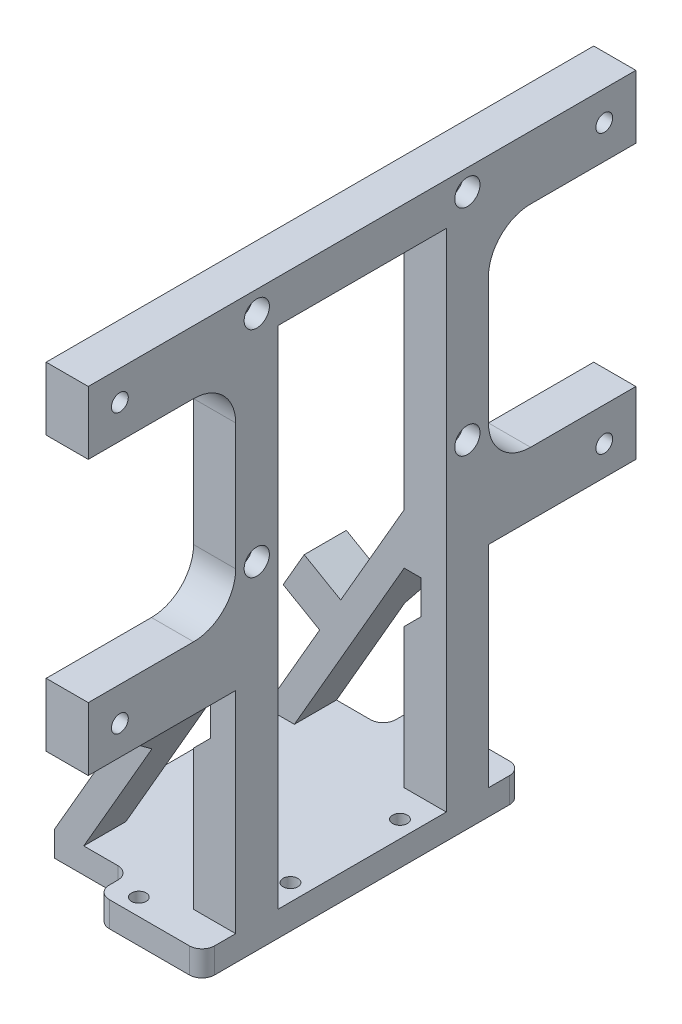
SolidWorks part; units mm, degrees
material "黄铜"
ref_plane "前视基准面" through (0, 0, 0) normal (0, 0, 1) x (1, 0, 0)
ref_plane "上视基准面" through (0, 0, 0) normal (0, 1, 0) x (1, 0, 0)
ref_plane "右视基准面" through (0, 0, 0) normal (1, 0, 0) x (0, 0, -1)
sketch "草图1" plane through (0, 0, 0) normal (0, 1, 0) x (1, 0, 0)
  line L1 (0, 0) -> (35, 0)
  line L2 (0, 0) -> (0, 60)
  line L3 (0, 60) -> (35, 60)
  line L4 (35, 0) -> (35, 60)
  line L5 (35, 60) -> (43, 60)
  line L6 (35, 60) -> (35, 0)
  line L7 (35, 0) -> (43, 0)
  line L8 (43, 60) -> (43, 0)
  line L9 (43, 60) -> (18, 60)
  line L10 (43, 60) -> (43, 68)
  line L11 (43, 68) -> (18, 68)
  line L12 (18, 60) -> (18, 68)
  line L13 (43, 0) -> (18, 0)
  line L14 (43, 0) -> (43, -8)
  line L15 (43, -8) -> (18, -8)
  line L16 (18, 0) -> (18, -8)
  dimension "D1" = 60
  dimension "D2" = 35
  dimension "D3" = 8
  dimension "D4" = 25
  dimension "D5" = 25
  dimension "D6" = 8
  dimension "D7" = 8
extrude "凸台-拉伸1" add sketch "草图1" along normal blind 6 contours L12 L3 L5 L10 L11 | L1 L4 L3 L2 | L8 L5 L4 L7 | L1 L16 L15 L14 L7
sketch "草图2" plane through (0, 6, 0) normal (0, 1, 0) x (1, 0, 0)
  line L0 (18, 64) -> (43, 64)
  line L1 (18, 60) -> (18, 68) construction
  line L2 (43, -8) -> (43, 68) construction
  line L3 (18, -4) -> (43, -4)
  line L4 (18, 0) -> (18, -8) construction
  line L5 (39, 68) -> (39, -8)
  line L6 (43, 68) -> (18, 68) construction
  line L7 (43, -8) -> (18, -8) construction
  point P6 (24, 64)
  point P11 (24, -4)
  point P18 (39, 43)
  point P19 (39, 17)
  dimension "D1" = 6
  dimension "D2" = 6
  dimension "D3" = 4
  dimension "D4" = 25
  dimension "D5" = 25
sketch "草图3" plane through (0, 6, 0) normal (0, 1, 0) x (1, 0, 0)
  point P0 (24, 64)
  point P3 (39, 43)
  point P6 (39, 17)
  point P9 (24, -4)
hole_wizard "孔1" positions "草图3" profile "草图4" legacy end condition through all
sketch "草图4" plane through (24, 6, -64) normal (1, 0, 0) x (0, 0, 1)
  line L0 (0, 0) -> (0, 6)
  line L1 (0, 6) -> (1.75, 6)
  line L2 (1.75, 6) -> (1.75, 0)
  line L3 (1.75, 0) -> (0, 0)
  line L4 (0, 110) -> (0, -10) construction
  dimension "直径" = 3.5
  dimension "深度" = 6
fillet "圆角1" radius 3 5 edges at (18, 3, -68) (43, 3, -68) (43, 3, 8) (18, 3, 8) (18, 3, 0)
sketch "草图5" plane through (0, 6, 0) normal (0, 1, 0) x (1, 0, 0)
  line L0 (43, -5) -> (43, 65) construction
  line L1 (43, 60) -> (33, 60)
  line L2 (43, 60) -> (43, 50)
  line L3 (43, 50) -> (33, 50)
  line L4 (33, 60) -> (33, 50)
  line L5 (0, 60) -> (18, 60) construction
  line L7 (43, 0) -> (33, 0)
  line L8 (43, 0) -> (43, 10)
  line L9 (43, 10) -> (33, 10)
  line L10 (33, 0) -> (33, 10)
  line L11 (0, 0) -> (15, 0) construction
  dimension "D1" = 10
  dimension "D2" = 10
  dimension "D3" = 10
  dimension "D4" = 10
extrude "凸台-拉伸2" add sketch "草图5" along normal blind 120
sketch "草图10" plane through (0, 126, 0) normal (0, 1, 0) x (1, 0, 0)
  line L1 (33, 60) -> (43, 60)
  line L2 (33, 60) -> (33, 0)
  line L3 (33, 0) -> (43, 0)
  line L4 (43, 60) -> (43, 0)
extrude "凸台-拉伸5" add sketch "草图10" along normal blind 10
sketch "草图11" plane through (43, 0, 0) normal (1, 0, 0) x (0, 0, -1)
  line L0 (0, 136) -> (0, 6) construction
  line L1 (0, 136) -> (10, 136)
  line L2 (0, 136) -> (0, 126)
  line L3 (0, 126) -> (10, 126)
  line L4 (10, 136) -> (10, 126)
  line L5 (50, 126) -> (60, 126)
  line L6 (50, 126) -> (50, 136)
  line L7 (50, 136) -> (60, 136)
  line L8 (60, 126) -> (60, 136)
  line L9 (0, 85) -> (10, 85)
  line L10 (0, 85) -> (0, 75)
  line L11 (0, 75) -> (10, 75)
  line L12 (10, 85) -> (10, 75)
  line L13 (10, 126) -> (10, 6) construction
  line L14 (50, 126) -> (50, 6) construction
  line L15 (50, 85) -> (60, 85)
  line L16 (50, 85) -> (50, 75)
  line L17 (50, 75) -> (60, 75)
  line L18 (60, 85) -> (60, 75)
  line L19 (60, 136) -> (60, 6) construction
  line L20 (0, 136) -> (10, 126)
  line L21 (60, 136) -> (50, 126)
  line L22 (0, 75) -> (10, 85)
  line L23 (60, 75) -> (50, 85)
  dimension "D1" = 61
  dimension "D2" = 10
  dimension "D3" = 61
  dimension "D4" = 10
sketch "草图12" plane through (43, 0, 0) normal (1, 0, 0) x (0, 0, -1)
  line L0 (0, 136) -> (10, 126) construction
  line L1 (60, 136) -> (50, 126) construction
  line L2 (60, 75) -> (50, 85) construction
  line L3 (0, 75) -> (10, 85) construction
  point P0 (5, 131)
  point P4 (55, 131)
  point P8 (55, 80)
  point P12 (5, 80)
hole_wizard "孔2" positions "草图12" profile "草图13" legacy end condition through all
sketch "草图13" plane through (43, 131, -5) normal (0, 1, 0) x (0, 0, -1)
  line L0 (0, 0) -> (0, 43)
  line L1 (0, 43) -> (1.75, 43)
  line L2 (1.75, 43) -> (1.75, 0)
  line L3 (1.75, 0) -> (0, 0)
  line L4 (0, 110) -> (0, -10) construction
  dimension "直径" = 3.5
  dimension "深度" = 43
sketch "草图14" plane through (43, 0, 0) normal (1, 0, 0) x (0, 0, -1)
  line L0 (0, 136) -> (10, 126) construction
  line L1 (0, 75) -> (10, 85) construction
  line L2 (60, 75) -> (50, 85) construction
  line L3 (60, 136) -> (50, 126) construction
  point P0 (5, 131)
  point P4 (5, 80)
  point P8 (55, 80)
  point P12 (55, 131)
hole_wizard "孔3" positions "草图14" profile "草图15" legacy
sketch "草图15" plane through (43, 131, -5) normal (0, 1, 0) x (0, 0, -1)
  line L0 (0, 0) -> (0, 4)
  line L1 (0, 4) -> (3, 4)
  line L2 (3, 4) -> (3, 0)
  line L3 (3, 0) -> (0, 0)
  line L4 (0, 110) -> (0, -10) construction
  dimension "直径" = 6
  dimension "深度" = 4
sketch "草图16" plane through (0, 0, -60) normal (0, 0, -1) x (-1, 0, 0)
  line L0 (-33, 6) -> (0, 6)
  line L1 (0, 6) -> (-33, 63.1577)
  line L2 (-33, 136) -> (-33, 6) construction
  line L3 (-33, 63.1577) -> (-33, 6)
  line L4 (-33, 51.1577) -> (-6.9282, 6)
  dimension "D1" = 60
  dimension "D2" = 6
extrude "凸台-拉伸6" add sketch "草图16" against normal blind 10 contours L3 L4 L0 L1
ref_plane "基准面1" through (0, 0, -30) normal (0, 0, 1) x (1, 0, 0)
mirror "镜向1" about plane through (0, 0, -30) normal (0, 0, 1) of "凸台-拉伸6"
sketch "草图17" plane through (33, 0, 0) normal (-1, 0, 0) x (0, 0, 1)
  line L0 (-30, -23.65) -> (-30, 23.65) construction
  line L1 (-95, 56) -> (35, 56)
  line L2 (-95, 56) -> (-95, 136)
  line L3 (-95, 136) -> (35, 136)
  line L4 (35, 56) -> (35, 136)
  line L5 (-95, 56) -> (35, 136)
  line L6 (-95, 136) -> (35, 56)
  line L7 (-60, 136) -> (0, 136) construction
  line L9 (-87.5, 129) -> (27.5, 129)
  line L10 (-87.5, 129) -> (-87.5, 63)
  line L11 (-87.5, 63) -> (27.5, 63)
  line L12 (27.5, 129) -> (27.5, 63)
  line L13 (-87.5, 129) -> (27.5, 63) construction
  line L14 (-87.5, 63) -> (27.5, 129) construction
  point P0 (-30, 96)
  point P9 (-30, 96)
  dimension "D1" = 130
  dimension "D2" = 80
  dimension "D3" = 115
  dimension "D4" = 66
sketch "草图18" plane through (33, 0, 0) normal (-1, 0, 0) x (0, 0, 1)
  line L0 (-95, 56) -> (-95, 136) construction
  line L1 (-60, 136) -> (-95, 136)
  line L2 (-60, 136) -> (-60, 121)
  line L3 (-60, 121) -> (-95, 121)
  line L4 (-95, 136) -> (-95, 121)
  line L5 (35, 56) -> (35, 136) construction
  line L6 (0, 136) -> (35, 136)
  line L7 (0, 136) -> (0, 121)
  line L8 (0, 121) -> (35, 121)
  line L9 (35, 136) -> (35, 121)
  line L10 (-60, 136) -> (-60, 63.1577) construction
  line L11 (-95, 56) -> (-60, 56)
  line L12 (-95, 56) -> (-95, 71)
  line L13 (-95, 71) -> (-60, 71)
  line L14 (-60, 56) -> (-60, 71)
  line L15 (0, 136) -> (0, 63.1577) construction
  line L16 (35, 56) -> (0, 56)
  line L17 (35, 56) -> (35, 71)
  line L18 (35, 71) -> (0, 71)
  line L19 (0, 56) -> (0, 71)
  dimension "D1" = 15
  dimension "D2" = 15
  dimension "D3" = 15
  dimension "D4" = 15
extrude "凸台-拉伸7" add sketch "草图18" against normal blind 10
sketch "草图19" plane through (33, 0, 0) normal (-1, 0, 0) x (0, 0, 1)
  point P0 (-87.5, 129)
  point P3 (27.5, 129)
  point P6 (27.5, 63)
  point P9 (-87.5, 63)
hole_wizard "孔4" positions "草图19" profile "草图20" legacy end condition through all
sketch "草图20" plane through (33, 129, -87.5) normal (0, 1, 0) x (0, 0, 1)
  line L0 (0, 0) -> (0, 10)
  line L1 (0, 10) -> (2, 10)
  line L2 (2, 10) -> (2, 0)
  line L3 (2, 0) -> (0, 0)
  line L4 (0, 110) -> (0, -10) construction
  dimension "直径" = 4
  dimension "深度" = 10
fillet "圆角2" radius 10 4 edges at (38, 121, 0) (38, 71, 0) (38, 71, -60) (38, 121, -60)
fillet "圆角3" radius 3 1 edges at (18, 3, -60)
sketch "草图21" plane through (-2.5981, 1.5, 0) normal (-0.866, 0.5, 0) x (0, 0, 1)
  line L0 (-60, 61.0596) -> (-50, 61.0596)
  line L1 (-60, 5.1962) -> (-60, 71.1962) construction
  line L2 (-50, 5.1962) -> (-50, 71.1962) construction
  line L3 (-10, 61.0596) -> (0, 61.0596)
  line L4 (-10, 5.1962) -> (-10, 71.1962) construction
  line L5 (0, 5.1962) -> (0, 71.1962) construction
  line L6 (-87.5, 71.0596) -> (27.5, 71.0596) construction
  line L7 (-70, 51.0596) -> (-60, 41.0596)
  line L8 (-60, 61.0596) -> (-70, 61.0596)
  line L9 (-60, 61.0596) -> (-60, 51.0596)
  line L10 (-60, 51.0596) -> (-70, 51.0596)
  line L11 (-70, 61.0596) -> (-70, 51.0596)
  line L12 (0, 61.0596) -> (10, 61.0596)
  line L13 (0, 61.0596) -> (0, 51.0596)
  line L14 (0, 51.0596) -> (10, 51.0596)
  line L15 (10, 61.0596) -> (10, 51.0596)
  line L16 (10, 51.0596) -> (0, 41.0596)
  line L17 (-60, 51.0596) -> (-60, 41.0596)
  line L18 (0, 51.0596) -> (0, 41.0596)
  line M11 (-60, 71.1962) -> (-60, 5.1962)
  dimension "D1" = 10
  dimension "D2" = 10
  dimension "D3" = 10
  dimension "D4" = 10
  dimension "D5" = 10
  dimension "D6" = 10
  dimension "D7" = 45
  dimension "D8" = 45
extrude "凸台-拉伸8" add sketch "草图21" against normal blind 6 contours L10 L7 M11 | L8 L11 L10 M11 | L15 L12 L13 L14 | L14 L18 L16
sketch "草图22" plane through (-2.5981, 1.5, 0) normal (-0.866, 0.5, 0) x (0, 0, 1)
  line L0 (-70, 56.0596) -> (10, 56.0596)
  line L1 (-70, 61.0596) -> (-70, 51.0596) construction
  line L2 (10, 61.0596) -> (10, 51.0596) construction
  line L3 (-30, 56.0596) -> (-62, 56.0596)
  line L4 (-30, 56.0596) -> (2, 56.0596)
  line L5 (-30, -23.65) -> (-30, 23.65) construction
  dimension "D1" = 32
  dimension "D2" = 32
sketch "草图23" plane through (-2.5981, 1.5, 0) normal (-0.866, 0.5, 0) x (0, 0, 1)
  point P0 (-62, 56.0596)
  point P3 (2, 56.0596)
hole_wizard "孔5" positions "草图23" profile "草图24" legacy end condition up to next
sketch "草图24" plane through (25.4317, 50.049, -62) normal (0, 0, 1) x (-0.5, -0.866, 0)
  line L0 (0, 0) -> (0, 6)
  line L1 (0, 6) -> (2, 6)
  line L2 (2, 6) -> (2, 0)
  line L3 (2, 0) -> (0, 0)
  line L4 (0, 110) -> (0, -10) construction
  dimension "直径" = 4
  dimension "深度" = 6
sketch "草图25" plane through (-2.5981, 1.5, 0) normal (-0.866, 0.5, 0) x (0, 0, 1)
  line L0 (-50, 5.1962) -> (-50, 71.1962) construction
  line L1 (-60, 41.0596) -> (-50, 41.0596)
  line L2 (-60, 41.0596) -> (-60, 31.0596)
  line L3 (-60, 31.0596) -> (-50, 31.0596)
  line L4 (-50, 41.0596) -> (-50, 31.0596)
  line L5 (-10, 5.1962) -> (-10, 71.1962) construction
  line L6 (0, 41.0596) -> (-10, 41.0596)
  line L7 (0, 41.0596) -> (0, 31.0596)
  line L8 (0, 31.0596) -> (-10, 31.0596)
  line L9 (-10, 41.0596) -> (-10, 31.0596)
  dimension "D1" = 10
  dimension "D2" = 10
extrude "凸台-拉伸9" add sketch "草图25" along normal blind 10
sketch "草图28" plane through (0, 0, -60) normal (0, 0, -1) x (-1, 0, 0)
  line L1 (-33, 51.1577) -> (-37, 51.1577)
  line L2 (-33, 51.1577) -> (-33, 43.1577)
  line L3 (-33, 43.1577) -> (-37, 43.1577)
  line L4 (-37, 51.1577) -> (-37, 43.1577)
  dimension "D1" = 4
  dimension "D2" = 8
extrude "切除-拉伸1" cut sketch "草图28" against normal through all
sketch "草图29" plane through (0, 0, -60) normal (0, 0, -1) x (-1, 0, 0)
  line L0 (-37, 43.1577) -> (-33, 43.1577)
  line L1 (-33, 43.1577) -> (-33, 39.1577)
  line L2 (-33, 43.1577) -> (-33, 6) construction
  line L3 (-33, 39.1577) -> (-37, 43.1577)
  dimension "D1" = 45
extrude "切除-拉伸2" cut sketch "草图29" against normal through all
